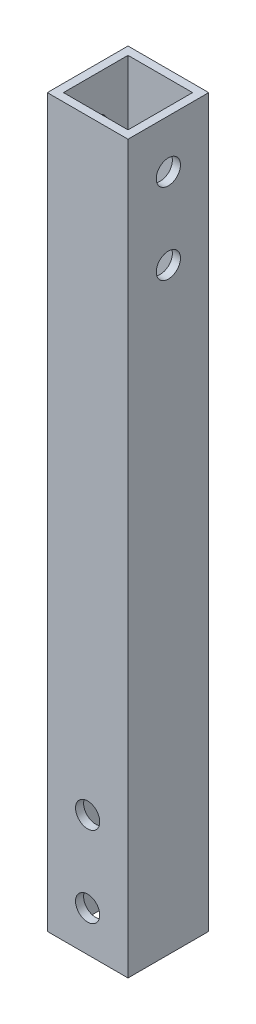
SolidWorks part; units mm, degrees
material "氧化铝"
ref_plane "前视基准面" through (0, 0, 0) normal (0, 0, 1) x (1, 0, 0)
ref_plane "上视基准面" through (0, 0, 0) normal (0, 1, 0) x (1, 0, 0)
ref_plane "右视基准面" through (0, 0, 0) normal (1, 0, 0) x (0, 0, -1)
other "Configuration Table"
sketch "草图1" plane through (0, 0, 0) normal (0, 1, 0) x (1, 0, 0)
  line L1 (-4, 4) -> (4, 4)
  line L2 (-4, 4) -> (-4, -4)
  line L3 (-4, -4) -> (4, -4)
  line L4 (4, 4) -> (4, -4)
  line L5 (-4, 4) -> (4, -4) construction
  line L6 (-4, -4) -> (4, 4) construction
  line L7 (-5, 5) -> (5, 5)
  line L8 (-5, 5) -> (-5, -5)
  line L9 (-5, -5) -> (5, -5)
  line L10 (5, 5) -> (5, -5)
  line L11 (-5, 5) -> (5, -5) construction
  line L12 (-5, -5) -> (5, 5) construction
  point P0 (0, 0)
  point P6 (0, 0)
  dimension "D1" = 1
  dimension "D2" = 1
  dimension "D3" = 10
  dimension "D4" = 10
extrude "凸台-拉伸1" add sketch "草图1" along normal blind 90
sketch "草图2" plane through (-5, 0, 0) normal (-1, 0, 0) x (0, 0, 1)
  line L0 (0, 84) -> (0, 74) construction
  line L1 (-5, 90) -> (5, 90) construction
  line L2 (0, 90) -> (0, 0) construction
  circle A0 centre (0, 84) radius 1.5
  circle A1 centre (0, 74) radius 1.5
  point P9 (0, 84)
  point P10 (-9.167, 84)
  dimension "D1" = 3
  dimension "D2" = 10
  dimension "D3" = 6
extrude "切除-拉伸1" cut sketch "草图2" against normal blind 30
sketch "草图3" plane through (0, 0, 5) normal (0, 0, 1) x (1, 0, 0)
  line L0 (0, 5) -> (0, 15) construction
  line L2 (0, 0) -> (0, 90) construction
  line L3 (-5, 90) -> (5, 90) construction
  line L4 (-5, 0) -> (5, 0) construction
  circle A0 centre (0, 5) radius 1.5
  circle A1 centre (0, 15) radius 1.5
  point P4 (0, 27.3499)
  dimension "D2" = 3
  dimension "D1" = 10
  dimension "D3" = 5
extrude "切除-拉伸2" cut sketch "草图3" against normal blind 30
